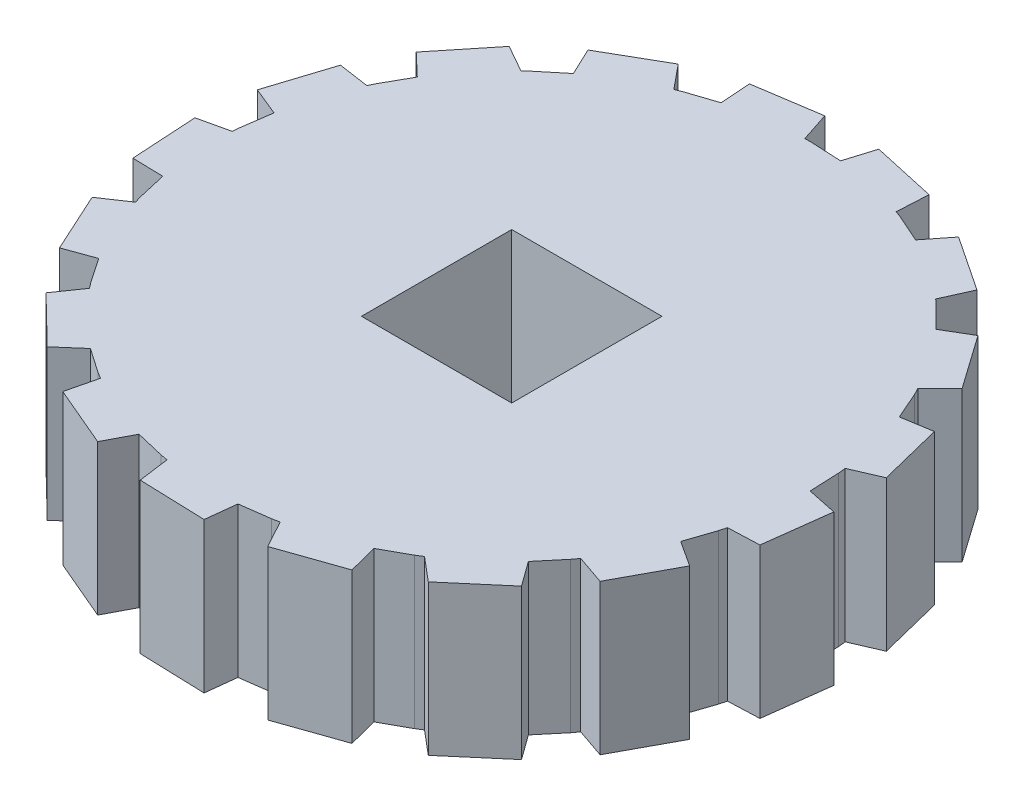
SolidWorks part; units mm, degrees
ref_plane "Front Plane" through (0, 0, 0) normal (0, 0, 1) x (1, 0, 0)
ref_plane "Top Plane" through (0, 0, 0) normal (0, 1, 0) x (1, 0, 0)
ref_plane "Right Plane" through (0, 0, 0) normal (1, 0, 0) x (0, 0, -1)
sketch "Belt Pulley" plane through (0, 0, 0) normal (0, 1, 0) x (1, 0, 0)
  line L0 (0, -18.2889) -> (0, 17.4478) construction
  line L1 (-3.175, -3.175) -> (3.175, -3.175)
  line L2 (-3.175, -3.175) -> (-3.175, 3.175)
  line L3 (-3.175, 3.175) -> (3.175, 3.175)
  line L4 (3.175, -3.175) -> (3.175, 3.175)
  line L5 (-3.175, -3.175) -> (3.175, 3.175) construction
  line L6 (-3.175, 3.175) -> (3.175, -3.175) construction
  line L7 (0, 12.7) -> (1.26, 12.6373)
  line L8 (1.26, 12.6373) -> (0, 0) construction
  line L9 (1.26, 12.6373) -> (1.64, 13.8734) construction
  line L10 (1.64, 13.8734) -> (4.368, 13.2696)
  line L11 (4.368, 13.2696) -> (4.7273, 13.1459) construction
  line L12 (0, 0) -> (4.7273, 13.1459) construction
  line L13 (8.8665, 10.7956) -> (8.3244, 9.5913)
  line L14 (1.26, 12.6373) -> (1.64, 13.8734)
  line L15 (4.368, 13.2696) -> (4.2975, 11.9508)
  line L16 (6.5409, 12.3441) -> (8.8665, 10.7956)
  line L17 (5.74, 11.3288) -> (6.5409, 12.3441)
  line L18 (4.5878, 11.8424) -> (5.74, 11.3288)
  line L19 (12.1676, 6.8637) -> (11.2271, 5.9365)
  line L20 (10.5584, 9.1477) -> (12.1676, 6.8637)
  line L21 (9.4449, 8.4903) -> (10.5584, 9.1477)
  line L22 (8.5559, 9.3854) -> (9.4449, 8.4903)
  line L23 (13.8254, 2.0047) -> (12.6135, 1.4799)
  line L24 (13.15, 4.7158) -> (13.8254, 2.0047)
  line L25 (11.8741, 4.505) -> (13.15, 4.7158)
  line L26 (11.3686, 5.6609) -> (11.8741, 4.505)
  line L27 (13.616, -3.125) -> (12.2963, -3.1765)
  line L28 (13.9655, -0.3529) -> (13.616, -3.125)
  line L29 (12.6997, -0.0886) -> (13.9655, -0.3529)
  line L30 (12.6458, 1.1718) -> (12.6997, -0.0886)
  line L31 (11.5677, -7.8326) -> (10.3185, -7.404)
  line L32 (12.895, -5.374) -> (11.5677, -7.8326)
  line L33 (11.8101, -4.6703) -> (12.895, -5.374)
  line L34 (12.2152, -3.4755) -> (11.8101, -4.6703)
  line L35 (7.9571, -11.4824) -> (6.9471, -10.6315)
  line L36 (10.0829, -9.6693) -> (7.9571, -11.4824)
  line L37 (9.3255, -8.6212) -> (10.0829, -9.6693)
  line L38 (10.1348, -7.6535) -> (9.3255, -8.6212)
  line L39 (3.2718, -13.5815) -> (2.6375, -12.4231)
  line L40 (5.909, -12.6588) -> (3.2718, -13.5815)
  line L41 (5.5814, -11.4078) -> (5.909, -12.6588)
  line L42 (6.6857, -10.7978) -> (5.5814, -11.4078)
  line L43 (-1.8553, -13.8463) -> (-2.0284, -12.537)
  line L44 (0.9372, -13.9385) -> (-1.8553, -13.8463)
  line L45 (1.0836, -12.6537) -> (0.9372, -13.9385)
  line L46 (2.3336, -12.4838) -> (1.0836, -12.6537)
  line L47 (-6.7319, -12.241) -> (-6.4203, -10.9576)
  line L48 (-4.1613, -13.3358) -> (-6.7319, -12.241)
  line L49 (-3.5607, -12.1906) -> (-4.1613, -13.3358)
  line L50 (-2.3336, -12.4838) -> (-3.5607, -12.1906)
  line L51 (-10.6993, -8.9826) -> (-9.9451, -7.8984)
  line L52 (-8.6978, -10.9321) -> (-10.6993, -8.9826)
  line L53 (-7.724, -10.0812) -> (-8.6978, -10.9321)
  line L54 (-6.6857, -10.7978) -> (-7.724, -10.0812)
  line L55 (-13.2216, -4.511) -> (-12.1268, -3.7725)
  line L56 (-12.0595, -7.0518) -> (-13.2216, -4.511)
  line L57 (-10.8441, -6.6102) -> (-12.0595, -7.0518)
  line L58 (-10.1348, -7.6535) -> (-10.8441, -6.6102)
  line L59 (-13.9584, 0.5698) -> (-12.6706, 0.863)
  line L60 (-13.7926, -2.2192) -> (-13.9584, 0.5698)
  line L61 (-12.4997, -2.2465) -> (-13.7926, -2.2192)
  line L62 (-12.2152, -3.4755) -> (-12.4997, -2.2465)
  line L63 (-12.8099, 5.5737) -> (-11.5033, 5.3819)
  line L64 (-13.6629, 2.9131) -> (-12.8099, 5.5737)
  line L65 (-12.4672, 2.4207) -> (-13.6629, 2.9131)
  line L66 (-12.6458, 1.1718) -> (-12.4672, 2.4207)
  line L67 (-9.9315, 9.8248) -> (-8.7823, 9.1739)
  line L68 (-11.6879, 7.652) -> (-9.9315, 9.8248)
  line L69 (-10.7509, 6.7609) -> (-11.6879, 7.652)
  line L70 (-11.3686, 5.6609) -> (-10.7509, 6.7609)
  line L71 (-5.7117, 12.749) -> (-4.8753, 11.727)
  line L72 (-8.1345, 11.3574) -> (-5.7117, 12.749)
  line L73 (-7.5826, 10.188) -> (-8.1345, 11.3574)
  line L74 (-8.5559, 9.3854) -> (-7.5826, 10.188)
  line L75 (-0.7205, 13.9514) -> (-0.3098, 12.6962)
  line L76 (-3.4824, 13.529) -> (-0.7205, 13.9514)
  line L77 (-3.3902, 12.2391) -> (-3.4824, 13.529)
  line L78 (-4.5878, 11.8424) -> (-3.3902, 12.2391)
  arc A0 (0, 12.7) -> (-0.3098, 12.6962) centre (0, 0) ccw
  circle A1 centre (0, 0) radius 13.97 construction
  arc A2 (-3.3902, 12.2391) -> (-4.8753, 11.727) centre (0, 0) ccw
  arc A3 (-7.5826, 10.188) -> (-8.7823, 9.1739) centre (0, 0) ccw
  arc A4 (5.74, 11.3288) -> (4.2975, 11.9508) centre (0, 0) ccw
  arc A5 (9.4449, 8.4903) -> (8.3244, 9.5913) centre (0, 0) ccw
  arc A6 (11.8741, 4.505) -> (11.2271, 5.9365) centre (0, 0) ccw
  arc A7 (12.6997, -0.0886) -> (12.6135, 1.4799) centre (0, 0) ccw
  arc A8 (11.8101, -4.6703) -> (12.2963, -3.1765) centre (0, 0) ccw
  arc A9 (-10.7509, 6.7609) -> (-11.5033, 5.3819) centre (0, 0) ccw
  arc A10 (-12.4672, 2.4207) -> (-12.6706, 0.863) centre (0, 0) ccw
  arc A11 (-12.4997, -2.2465) -> (-12.1268, -3.7725) centre (0, 0) ccw
  arc A12 (-10.8441, -6.6102) -> (-9.9451, -7.8984) centre (0, 0) ccw
  arc A13 (-7.724, -10.0812) -> (-6.4203, -10.9576) centre (0, 0) ccw
  arc A14 (-3.5607, -12.1906) -> (-2.0284, -12.537) centre (0, 0) ccw
  arc A15 (1.0836, -12.6537) -> (2.6375, -12.4231) centre (0, 0) ccw
  arc A16 (5.5814, -11.4078) -> (6.9471, -10.6315) centre (0, 0) ccw
  arc A17 (9.3255, -8.6212) -> (10.3185, -7.404) centre (0, 0) ccw
  point P98 (0, 0)
  dimension "D1" = 25.4
  dimension "D9" = 27.94
  dimension "D2" = 6.35
  dimension "D3" = 6.35
  dimension "D4" = 0.38
  dimension "D5" = 2.794
  dimension "D6" = 1.26
  dimension "D7" = 0.38
  dimension "D8" = 17
extrude "Boss-Extrude1" add sketch "Belt Pulley" along normal blind 6.35 contours A0 L4 L1 L2 L3
equation "\"Ball Diameter\"= 1.75in"
equation "\"Sheet Thickness\"= 0.25in"
equation "\"Screw Diameter\"= .17in"
equation "\"Robot Diameter\"= 14in"
equation "\"Castor Screw Diameter\"= 0.22in"
equation "\"Wheel Diameter\" = 4in"
equation "\"Nut Diameter\" = 8.4mm"
equation "\"Nut Height\" = 2.9mm"
equation "\"Screw Height\" = 0.55in"
equation "\"Pulley Diameter\" = 1in"
equation "\"Reactor Height\" = 14in"
equation "\"D1@Belt Pulley\"=\"Pulley Diameter\""
equation "\"D2@Belt Pulley\"=\"Sheet Thickness\""
equation "\"D3@Belt Pulley\"=\"Sheet Thickness\""
equation "\"D1@Boss-Extrude1\"=\"Sheet Thickness\""
equation "\"D9@Belt Pulley\"=\"Pulley Diameter\" + 0.1in"
